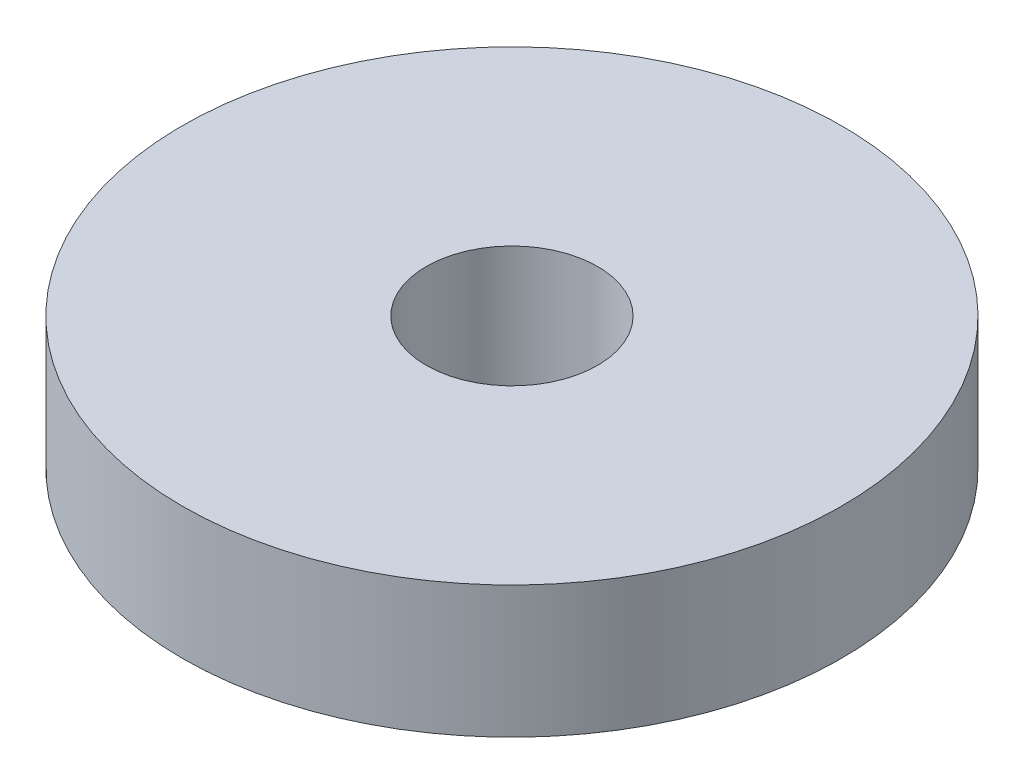
SolidWorks part; units mm, degrees
ref_plane "Front Plane" through (0, 0, 0) normal (0, 0, 1) x (1, 0, 0)
ref_plane "Top Plane" through (0, 0, 0) normal (0, 1, 0) x (1, 0, 0)
ref_plane "Right Plane" through (0, 0, 0) normal (1, 0, 0) x (0, 0, -1)
sketch "Sketch1" plane through (0, 0, 0) normal (0, 1, 0) x (1, 0, 0)
  circle A0 centre (0, 0) radius 1.651
  circle A1 centre (0, 0) radius 6.35
  dimension "D1" = 3.302
  dimension "D2" = 12.7
extrude "Boss-Extrude1" add sketch "Sketch1" along normal blind 2.54
